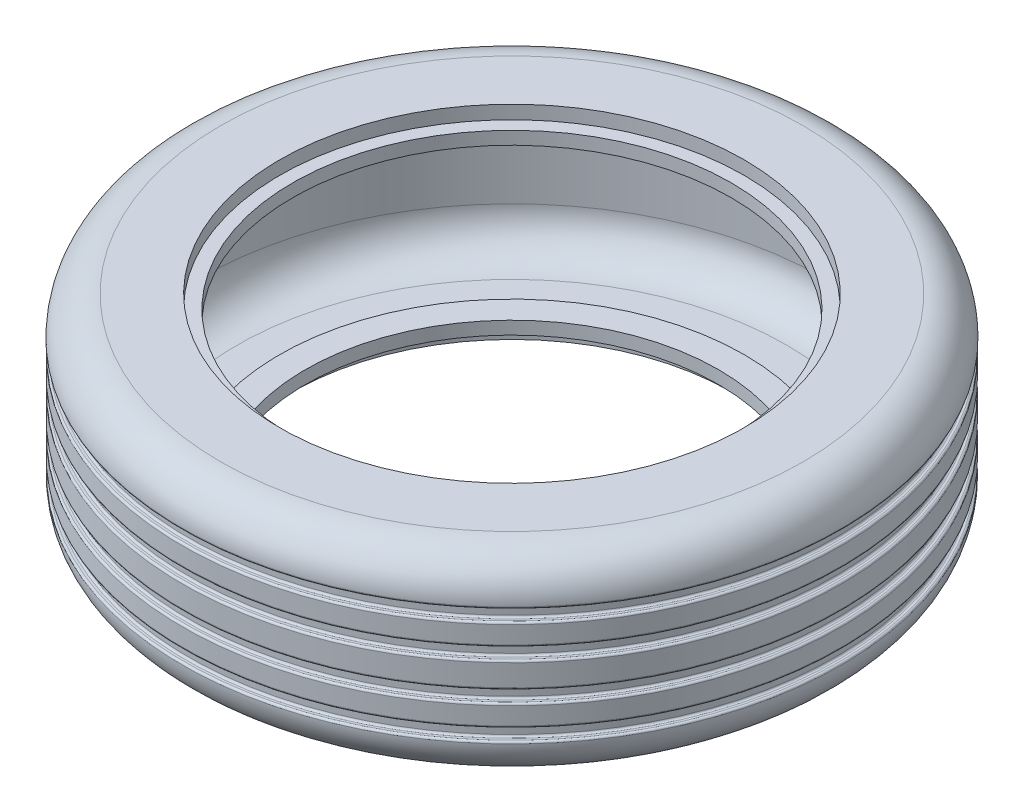
SolidWorks part; units mm, degrees
material "Natural Rubber"
ref_plane "Front Plane" through (0, 0, 0) normal (0, 0, 1) x (1, 0, 0)
ref_plane "Top Plane" through (0, 0, 0) normal (0, 1, 0) x (1, 0, 0)
ref_plane "Right Plane" through (0, 0, 0) normal (1, 0, 0) x (0, 0, -1)
sketch "Sketch1" plane through (0, 0, 0) normal (1, 0, 0) x (0, 0, -1)
  line L0 (135.6119, -170.3455) -> (135.6119, -0.954) construction
  line L2 (-204.0326, 50.4745) -> (-204.0326, 70.4745)
  line L3 (-204.0326, 70.4745) -> (-224.0326, 70.4745)
  line L4 (-224.0326, 70.4745) -> (-224.0326, 91.3862)
  line L5 (-224.0326, 91.3862) -> (-315.4808, 91.3862)
  line L7 (-315.0326, -210.3455) -> (-204.3881, -210.3455)
  line L8 (-204.3881, -210.3455) -> (-204.3881, -190.3455)
  line L9 (-204.3881, -190.3455) -> (-184.3881, -190.3455)
  line L10 (-184.3881, -190.3455) -> (-184.3881, -170.3455)
  line L11 (-184.3881, -170.3455) -> (-224.3881, -170.3455)
  line L12 (-224.3881, -170.3455) -> (-224.3881, -190.3455)
  line L13 (-224.3881, -190.3455) -> (-290.0326, -190.3455)
  line L14 (-349.4426, -130.9355) -> (-349.4426, 11.0645)
  line L16 (-204.0326, 50.4745) -> (-244.0326, 50.4745)
  line L17 (-244.0326, 50.4745) -> (-244.0326, 70.4745)
  line L18 (-244.0326, 70.4745) -> (-290.0326, 70.4745)
  line L20 (-374.4257, -59.9428) -> (-576.2151, -59.9428) construction
  line L21 (-371.1983, 29.0572) -> (-367.954, 29.0572)
  line L23 (-371.4425, 11.0572) -> (-367.954, 11.0572)
  line L24 (-364.954, 26.0572) -> (-364.954, 14.0572)
  line L25 (-371.4425, -22.1832) -> (-367.954, -22.1832)
  line L27 (-371.4425, -40.1832) -> (-367.954, -40.1832)
  line L28 (-364.954, -25.1832) -> (-364.954, -37.1832)
  line L29 (-371.4425, -79.7024) -> (-367.954, -79.7024)
  line L30 (-364.954, -94.7024) -> (-364.954, -82.7024)
  line L31 (-371.4425, -97.7024) -> (-367.954, -97.7024)
  line L33 (-371.4425, -130.9428) -> (-367.954, -130.9428)
  line L34 (-364.954, -145.9428) -> (-364.954, -133.9428)
  line L35 (-371.4336, -148.9428) -> (-367.954, -148.9428)
  line L37 (-374.4425, 8.0572) -> (-374.4425, -19.1832)
  line L38 (-374.4425, -43.1832) -> (-374.4425, -76.7024)
  line L39 (-374.4425, -100.7024) -> (-374.4425, -127.9428)
  arc A0 (-374.4331, -151.9964) -> (-315.0326, -210.3455) centre (-315.0326, -150.9355) ccw
  arc A1 (-349.4426, -130.9355) -> (-290.0326, -190.3455) centre (-290.0326, -130.9355) ccw
  arc A2 (-374.8908, 31.9762) -> (-315.4808, 91.3862) centre (-315.4808, 31.9762) cw
  arc A3 (-349.4426, 11.0645) -> (-290.0326, 70.4745) centre (-290.0326, 11.0645) cw
  arc A4 (-371.4425, -22.1832) -> (-374.4425, -19.1832) centre (-371.4425, -19.1832) cw
  arc A5 (-371.4425, -40.1832) -> (-374.4425, -43.1832) centre (-371.4425, -43.1832) ccw
  arc A6 (-371.4425, -79.7024) -> (-374.4425, -76.7024) centre (-371.4425, -76.7024) cw
  arc A7 (-371.4425, -97.7024) -> (-374.4425, -100.7024) centre (-371.4425, -100.7024) ccw
  arc A8 (-374.4331, -151.9964) -> (-371.4336, -148.9428) centre (-371.4336, -151.9428) cw
  arc A9 (-371.4425, -130.9428) -> (-374.4425, -127.9428) centre (-371.4425, -127.9428) cw
  arc A10 (-364.954, -145.9428) -> (-367.954, -148.9428) centre (-367.954, -145.9428) cw
  arc A11 (-367.954, -130.9428) -> (-364.954, -133.9428) centre (-367.954, -133.9428) cw
  arc A12 (-364.954, -94.7024) -> (-367.954, -97.7024) centre (-367.954, -94.7024) cw
  arc A13 (-367.954, -79.7024) -> (-364.954, -82.7024) centre (-367.954, -82.7024) cw
  arc A14 (-367.954, -40.1832) -> (-364.954, -37.1832) centre (-367.954, -37.1832) ccw
  arc A15 (-367.954, -22.1832) -> (-364.954, -25.1832) centre (-367.954, -25.1832) cw
  arc A16 (-367.954, 11.0572) -> (-364.954, 14.0572) centre (-367.954, 14.0572) ccw
  arc A17 (-367.954, 29.0572) -> (-364.954, 26.0572) centre (-367.954, 26.0572) cw
  arc A18 (-371.4425, 11.0572) -> (-374.4425, 8.0572) centre (-371.4425, 8.0572) ccw
  arc A19 (-374.8908, 31.9762) -> (-371.1983, 29.0572) centre (-371.8908, 31.9762) ccw
  point P23 (-374.0326, -208.6138)
  point P26 (-349.4426, -190.3455)
  point P29 (-374.0326, 91.3862)
  point P47 (-374.4425, 11.0572)
  point P55 (-374.4425, -40.1832)
  point P60 (-374.4425, -97.7024)
  point P68 (-364.954, -148.9428)
  point P71 (-364.954, -130.9428)
  point P74 (-364.954, -97.7024)
  point P77 (-364.954, -79.7024)
  point P80 (-364.954, -40.1832)
  point P83 (-364.954, -22.1832)
  point P86 (-364.954, 11.0572)
  point P89 (-364.954, 29.0572)
  dimension "D14" = 0
  dimension "D11" = 3
  dimension "D16" = 3
  dimension "D10" = 59.41
  dimension "D17" = 3
  dimension "D18" = 59.41
  dimension "D19" = 59.41
  dimension "D20" = 59.41
  dimension "D1" = 20
  dimension "D2" = 20
  dimension "D3" = 150
  dimension "D4" = 20
  dimension "D5" = 20
  dimension "D6" = 20
  dimension "D7" = 40
  dimension "D8" = 20
  dimension "D9" = 300
  dimension "D12" = 40
  dimension "D13" = 320
  dimension "D15" = 0
revolve "Revolve1" add sketch "Sketch1" angle 360 about L0
